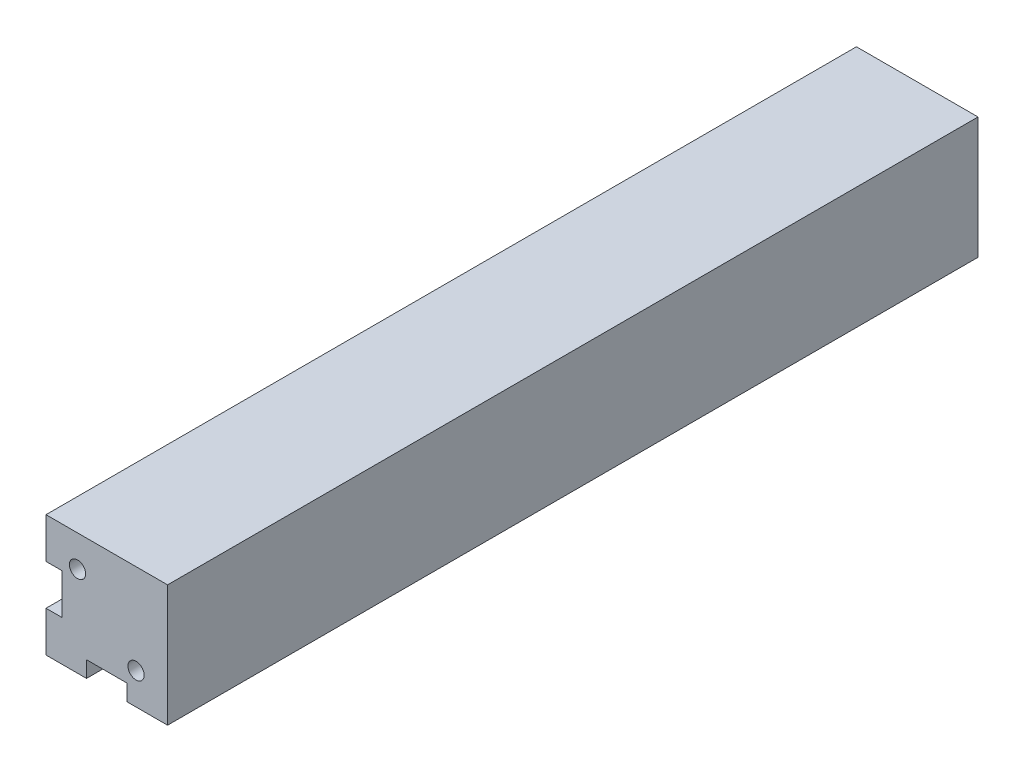
SolidWorks part; units mm, degrees
ref_plane "Alzado" through (0, 0, 0) normal (0, 0, 1) x (1, 0, 0)
ref_plane "Planta" through (0, 0, 0) normal (0, 1, 0) x (1, 0, 0)
ref_plane "Vista lateral" through (0, 0, 0) normal (1, 0, 0) x (0, 0, -1)
sketch "Croquis1" plane through (0, 0, 0) normal (0, 0, 1) x (1, 0, 0)
  line L1 (-15, -15) -> (15, -15)
  line L2 (-15, -15) -> (-15, 15)
  line L3 (-15, 15) -> (15, 15)
  line L4 (15, -15) -> (15, 15)
  line L5 (-15, -15) -> (15, 15) construction
  line L6 (-15, 15) -> (15, -15) construction
  point P0 (0, 0)
  dimension "D1" = 30
extrude "Saliente-Extruir1" add sketch "Croquis1" along normal blind 200
sketch "Croquis2" plane through (0, 0, 200) normal (0, 0, 1) x (1, 0, 0)
  line L0 (-15, 15) -> (15, -15) construction
  line L1 (-15, -15) -> (15, 15) construction
  circle A1 centre (-7.2218, 7.2218) radius 2
  circle A2 centre (7.2218, -7.2218) radius 2
  dimension "D1" = 11
extrude "Cortar-Extruir1" cut sketch "Croquis2" against normal blind 25
sketch "Croquis4" plane through (0, 0, 0) normal (0, 0, -1) x (-1, 0, 0)
  circle A0 centre (0, 0) radius 2
extrude "Cortar-Extruir3" cut sketch "Croquis4" against normal blind 25
sketch "Croquis5" plane through (0, 0, 0) normal (0, 0, -1) x (-1, 0, 0)
  line L0 (0, 0) -> (0, -15) construction
  line L1 (15, -15) -> (-15, -15) construction
  line L2 (0, 0) -> (15, 0) construction
  line L3 (-5, -19) -> (5, -19)
  line L4 (-5, -19) -> (-5, -11)
  line L5 (-5, -11) -> (5, -11)
  line L6 (5, -19) -> (5, -11)
  line L7 (-5, -19) -> (5, -11) construction
  line L8 (-5, -11) -> (5, -19) construction
  line L9 (15, 15) -> (15, -15) construction
  line L11 (11, -5) -> (19, -5)
  line L12 (11, -5) -> (11, 5)
  line L13 (11, 5) -> (19, 5)
  line L14 (19, -5) -> (19, 5)
  line L15 (11, -5) -> (19, 5) construction
  line L16 (11, 5) -> (19, -5) construction
  dimension "D1" = 10
  dimension "D2" = 8
  dimension "D3" = 8
  dimension "D4" = 10
extrude "Cortar-Extruir4" cut sketch "Croquis5" against normal blind 200
